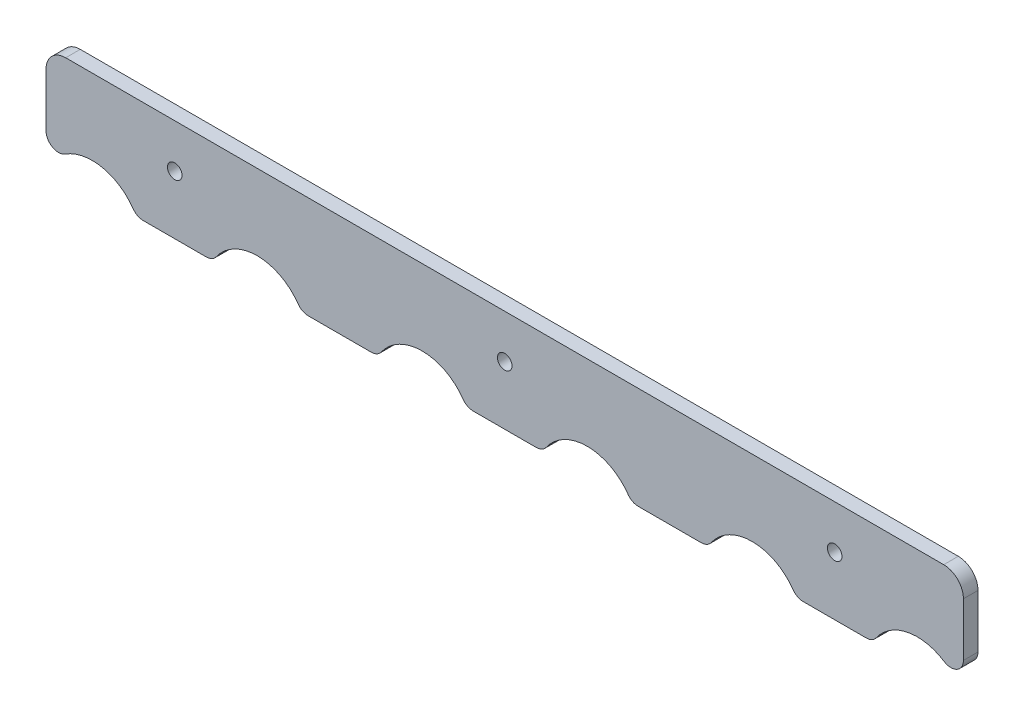
SolidWorks part; units mm, degrees
material "3003-H14"
ref_plane "X-Y Datum" through (0, 0, 0) normal (0, 0, 1) x (1, 0, 0)
ref_plane "X-Z Datum" through (0, 0, 0) normal (0, 1, 0) x (1, 0, 0)
ref_plane "Y-Z Datum" through (0, 0, 0) normal (1, 0, 0) x (0, 0, -1)
sketch "Sketch3" plane through (0, 0, 0) normal (0, 0, 1) x (1, 0, 0)
  line L1 (0, 0) -> (156.4633, 0) construction
  line L2 (0, 0) -> (0, 56.3098) construction
  line L3 (0, 56.3098) -> (156.4633, 56.3098) construction
  line L4 (156.4633, 0) -> (156.4633, 56.3098) construction
  line L5 (4.075, 10.775) -> (4.075, 28.535)
  line L6 (4.075, 28.535) -> (132.475, 28.535)
  line L7 (132.475, 28.535) -> (132.475, 10.775)
  line L9 (4.075, 13.775) -> (132.475, 13.775)
  line L10 (10.775, 10.775) -> (33.775, 10.775) construction
  line L11 (56.775, 10.775) -> (33.775, 10.775) construction
  line L48 (56.775, 10.775) -> (125.775, 10.775) construction
  circle A0 centre (10.775, 10.775) radius 10.775 construction
  circle A1 centre (33.775, 10.775) radius 10.775 construction
  circle A5 centre (56.775, 10.775) radius 10.775 construction
  circle A6 centre (10.775, 10.775) radius 4.7 construction
  circle A7 centre (33.775, 10.775) radius 4.7 construction
  circle A8 centre (56.775, 10.775) radius 4.7 construction
  circle A12 centre (79.775, 10.775) radius 10.775 construction
  circle A13 centre (79.775, 10.775) radius 4.7 construction
  circle A14 centre (102.775, 10.775) radius 10.775 construction
  circle A15 centre (102.775, 10.775) radius 4.7 construction
  circle A16 centre (125.775, 10.775) radius 10.775 construction
  circle A17 centre (125.775, 10.775) radius 4.7 construction
  circle A18 centre (125.775, 10.775) radius 10.775 construction
  circle A19 centre (102.775, 10.775) radius 10.775 construction
  circle A20 centre (79.775, 10.775) radius 10.775 construction
  circle A25 centre (10.775, 10.775) radius 6.7
  circle A26 centre (33.775, 10.775) radius 6.7
  circle A27 centre (56.775, 10.775) radius 6.7
  circle A28 centre (79.775, 10.775) radius 6.7
  circle A29 centre (102.775, 10.775) radius 6.7
  circle A30 centre (125.775, 10.775) radius 6.7
  dimension "D1" = 21.55
  dimension "D9" = 9.4
  dimension "D2" = 23
  dimension "D3" = 2
  dimension "D4" = 14.76
  dimension "D8" = 23
  dimension "D11" = 23
  dimension "D5" = 3
  dimension "D10" = 4
  dimension "D7" = 5
extrude "Boss-Extrude1" add sketch "Sketch3" along normal blind 2.032
fillet "Fillet1" radius 3 2 edges at (4.075, 28.535, 1.016) (132.475, 28.535, 1.016)
fillet "Fillet2" radius 2 12 edges at (132.475, 10.775, 1.016) (119.7842, 13.775, 1.016) (108.7658, 13.775, 1.016) (96.7842, 13.775, 1.016) (85.7658, 13.775, 1.016) (73.7842, 13.775, 1.016) (62.7658, 13.775, 1.016) (50.7842, 13.775, 1.016) (39.7658, 13.775, 1.016) (27.7842, 13.775, 1.016) (16.7658, 13.775, 1.016) (4.075, 10.775, 1.016)
sketch "Sketch4" plane through (0, 0, 0) normal (0, 0, -1) x (-1, 0, 0)
  line L0 (-132.475, 22.185) -> (-4.075, 22.185) construction
  line L1 (-132.475, 25.535) -> (-132.475, 18.0962) construction
  line L2 (-4.075, 18.0962) -> (-4.075, 25.535) construction
  line L3 (-7.075, 28.535) -> (-129.475, 28.535) construction
  line L4 (-68.275, 28.535) -> (-68.275, 13.775) construction
  line L5 (-63.8947, 13.775) -> (-72.6553, 13.775) construction
  line L6 (-68.275, 22.185) -> (-4.075, 22.185) construction
  line L7 (-22.275, 13.775) -> (-22.275, 28.535) construction
  line L8 (-17.8947, 13.775) -> (-26.6553, 13.775) construction
  line L9 (-114.275, 13.775) -> (-114.275, 28.535) construction
  line L10 (-109.8947, 13.775) -> (-118.6553, 13.775) construction
  circle A0 centre (-22.275, 22.185) radius 1.016
  circle A1 centre (-68.275, 22.185) radius 1.016
  circle A3 centre (-114.275, 22.185) radius 1.016
  point P30 (-68.275, 22.185)
  dimension "D1" = 2.032
  dimension "D2" = 6.35
extrude "Cut-Extrude1" cut sketch "Sketch4" against normal through all
sketch "Sketch5" plane through (0, 0, 2.032) normal (0, 0, 1) x (1, 0, 0)
  line L0 (4.329, 25.535) -> (4.329, 18.0962)
  line L1 (17.8947, 14.029) -> (26.6553, 14.029)
  line L2 (40.8947, 14.029) -> (49.6553, 14.029)
  line L3 (63.8947, 14.029) -> (72.6553, 14.029)
  line L4 (86.8947, 14.029) -> (95.6553, 14.029)
  line L5 (109.8947, 14.029) -> (118.6553, 14.029)
  line L6 (132.221, 18.0962) -> (132.221, 25.535)
  line L7 (129.475, 28.281) -> (7.075, 28.281)
  line L8 (132.475, 18.0962) -> (132.475, 25.535)
  line L9 (129.475, 28.535) -> (7.075, 28.535)
  line L10 (4.075, 25.535) -> (4.075, 18.0962)
  line L11 (17.8947, 13.775) -> (26.6553, 13.775)
  line L12 (40.8947, 13.775) -> (49.6553, 13.775)
  line L13 (63.8947, 13.775) -> (72.6553, 13.775)
  line L14 (86.8947, 13.775) -> (95.6553, 13.775)
  line L15 (109.8947, 13.775) -> (118.6553, 13.775)
  line L16 (132.475, 18.0962) -> (132.475, 25.535)
  line L17 (129.475, 28.535) -> (7.075, 28.535)
  line L18 (4.075, 25.535) -> (4.075, 18.0962)
  line L19 (17.8947, 13.775) -> (26.6553, 13.775)
  line L20 (40.8947, 13.775) -> (49.6553, 13.775)
  line L21 (63.8947, 13.775) -> (72.6553, 13.775)
  line L22 (86.8947, 13.775) -> (95.6553, 13.775)
  line L23 (109.8947, 13.775) -> (118.6553, 13.775)
  arc A0 (4.329, 18.0962) -> (7.0182, 16.6269) centre (6.075, 18.0962) ccw
  arc A1 (16.4658, 14.7716) -> (7.0182, 16.6269) centre (10.775, 10.775) ccw
  arc A2 (16.4658, 14.7716) -> (17.8947, 14.029) centre (17.8947, 15.775) ccw
  arc A3 (26.6553, 14.029) -> (28.0842, 14.7716) centre (26.6553, 15.775) ccw
  arc A4 (39.4658, 14.7716) -> (28.0842, 14.7716) centre (33.775, 10.775) ccw
  arc A5 (39.4658, 14.7716) -> (40.8947, 14.029) centre (40.8947, 15.775) ccw
  arc A6 (49.6553, 14.029) -> (51.0842, 14.7716) centre (49.6553, 15.775) ccw
  arc A7 (62.4658, 14.7716) -> (51.0842, 14.7716) centre (56.775, 10.775) ccw
  arc A8 (62.4658, 14.7716) -> (63.8947, 14.029) centre (63.8947, 15.775) ccw
  arc A9 (72.6553, 14.029) -> (74.0842, 14.7716) centre (72.6553, 15.775) ccw
  arc A10 (85.4658, 14.7716) -> (74.0842, 14.7716) centre (79.775, 10.775) ccw
  arc A11 (85.4658, 14.7716) -> (86.8947, 14.029) centre (86.8947, 15.775) ccw
  arc A12 (95.6553, 14.029) -> (97.0842, 14.7716) centre (95.6553, 15.775) ccw
  arc A13 (108.4658, 14.7716) -> (97.0842, 14.7716) centre (102.775, 10.775) ccw
  arc A14 (108.4658, 14.7716) -> (109.8947, 14.029) centre (109.8947, 15.775) ccw
  arc A15 (118.6553, 14.029) -> (120.0842, 14.7716) centre (118.6553, 15.775) ccw
  arc A16 (129.5318, 16.6269) -> (120.0842, 14.7716) centre (125.775, 10.775) ccw
  arc A17 (129.5318, 16.6269) -> (132.221, 18.0962) centre (130.475, 18.0962) ccw
  arc A18 (132.221, 25.535) -> (129.475, 28.281) centre (129.475, 25.535) ccw
  arc A19 (7.075, 28.281) -> (4.329, 25.535) centre (7.075, 25.535) ccw
  arc A20 (129.3945, 16.4132) -> (120.292, 14.6256) centre (125.775, 10.775) ccw
  arc A21 (129.3945, 16.4132) -> (132.475, 18.0962) centre (130.475, 18.0962) ccw
  arc A22 (132.475, 25.535) -> (129.475, 28.535) centre (129.475, 25.535) ccw
  arc A23 (7.075, 28.535) -> (4.075, 25.535) centre (7.075, 25.535) ccw
  arc A24 (4.075, 18.0962) -> (7.1555, 16.4132) centre (6.075, 18.0962) ccw
  arc A25 (16.258, 14.6256) -> (7.1555, 16.4132) centre (10.775, 10.775) ccw
  arc A26 (16.258, 14.6256) -> (17.8947, 13.775) centre (17.8947, 15.775) ccw
  arc A27 (26.6553, 13.775) -> (28.292, 14.6256) centre (26.6553, 15.775) ccw
  arc A28 (39.258, 14.6256) -> (28.292, 14.6256) centre (33.775, 10.775) ccw
  arc A29 (39.258, 14.6256) -> (40.8947, 13.775) centre (40.8947, 15.775) ccw
  arc A30 (49.6553, 13.775) -> (51.292, 14.6256) centre (49.6553, 15.775) ccw
  arc A31 (62.258, 14.6256) -> (51.292, 14.6256) centre (56.775, 10.775) ccw
  arc A32 (62.258, 14.6256) -> (63.8947, 13.775) centre (63.8947, 15.775) ccw
  arc A33 (72.6553, 13.775) -> (74.292, 14.6256) centre (72.6553, 15.775) ccw
  arc A34 (85.258, 14.6256) -> (74.292, 14.6256) centre (79.775, 10.775) ccw
  arc A35 (85.258, 14.6256) -> (86.8947, 13.775) centre (86.8947, 15.775) ccw
  arc A36 (95.6553, 13.775) -> (97.292, 14.6256) centre (95.6553, 15.775) ccw
  arc A37 (108.258, 14.6256) -> (97.292, 14.6256) centre (102.775, 10.775) ccw
  arc A38 (108.258, 14.6256) -> (109.8947, 13.775) centre (109.8947, 15.775) ccw
  arc A39 (118.6553, 13.775) -> (120.292, 14.6256) centre (118.6553, 15.775) ccw
  arc A40 (129.3945, 16.4132) -> (120.292, 14.6256) centre (125.775, 10.775) ccw
  arc A41 (129.3945, 16.4132) -> (132.475, 18.0962) centre (130.475, 18.0962) ccw
  arc A42 (132.475, 25.535) -> (129.475, 28.535) centre (129.475, 25.535) ccw
  arc A43 (7.075, 28.535) -> (4.075, 25.535) centre (7.075, 25.535) ccw
  arc A44 (4.075, 18.0962) -> (7.1555, 16.4132) centre (6.075, 18.0962) ccw
  arc A45 (16.258, 14.6256) -> (7.1555, 16.4132) centre (10.775, 10.775) ccw
  arc A46 (16.258, 14.6256) -> (17.8947, 13.775) centre (17.8947, 15.775) ccw
  arc A47 (26.6553, 13.775) -> (28.292, 14.6256) centre (26.6553, 15.775) ccw
  arc A48 (39.258, 14.6256) -> (28.292, 14.6256) centre (33.775, 10.775) ccw
  arc A49 (39.258, 14.6256) -> (40.8947, 13.775) centre (40.8947, 15.775) ccw
  arc A50 (49.6553, 13.775) -> (51.292, 14.6256) centre (49.6553, 15.775) ccw
  arc A51 (62.258, 14.6256) -> (51.292, 14.6256) centre (56.775, 10.775) ccw
  arc A52 (62.258, 14.6256) -> (63.8947, 13.775) centre (63.8947, 15.775) ccw
  arc A53 (72.6553, 13.775) -> (74.292, 14.6256) centre (72.6553, 15.775) ccw
  arc A54 (85.258, 14.6256) -> (74.292, 14.6256) centre (79.775, 10.775) ccw
  arc A55 (85.258, 14.6256) -> (86.8947, 13.775) centre (86.8947, 15.775) ccw
  arc A56 (95.6553, 13.775) -> (97.292, 14.6256) centre (95.6553, 15.775) ccw
  arc A57 (108.258, 14.6256) -> (97.292, 14.6256) centre (102.775, 10.775) ccw
  arc A58 (108.258, 14.6256) -> (109.8947, 13.775) centre (109.8947, 15.775) ccw
  arc A59 (118.6553, 13.775) -> (120.292, 14.6256) centre (118.6553, 15.775) ccw
  dimension "D1" = 0
  dimension "D2" = 0.254
extrude "Cut-Extrude2" cut sketch "Sketch5" against normal through all
